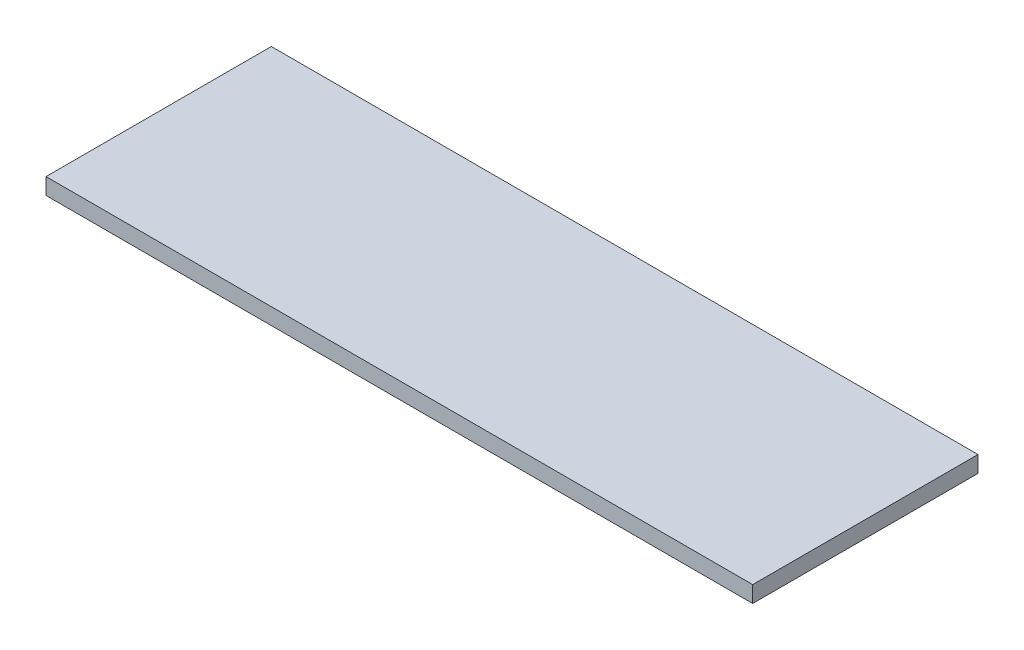
SolidWorks part; units mm, degrees
ref_plane "Front Plane" through (0, 0, 0) normal (0, 0, 1) x (1, 0, 0)
ref_plane "Top Plane" through (0, 0, 0) normal (0, 1, 0) x (1, 0, 0)
ref_plane "Right Plane" through (0, 0, 0) normal (1, 0, 0) x (0, 0, -1)
sketch "Sketch1" plane through (0, 0, 0) normal (0, 1, 0) x (1, 0, 0)
  line L1 (0, 0) -> (-69, 0)
  line L2 (0, 0) -> (0, 22)
  line L3 (0, 22) -> (-69, 22)
  line L4 (-69, 0) -> (-69, 22)
  dimension "D1" = 22
  dimension "D2" = 69
extrude "Boss-Extrude1" add sketch "Sketch1" along normal blind 1.6
